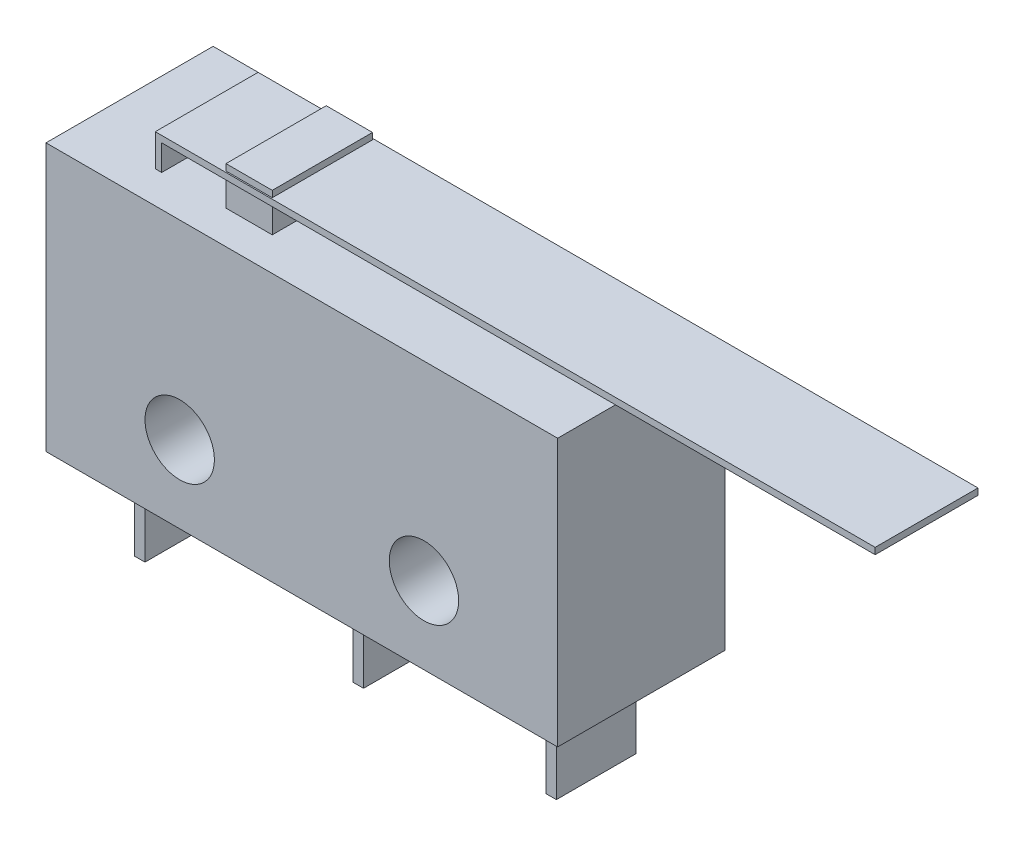
SolidWorks part; units mm, degrees
ref_plane "Plan de face" through (0, 0, 0) normal (0, 0, 1) x (1, 0, 0)
ref_plane "Plan de dessus" through (0, 0, 0) normal (0, 1, 0) x (1, 0, 0)
ref_plane "Plan de droite" through (0, 0, 0) normal (1, 0, 0) x (0, 0, -1)
sketch "Esquisse1" plane through (0, 0, 0) normal (0, 0, 1) x (1, 0, 0)
  line L1 (-9.95, 5.2) -> (9.95, 5.2)
  line L2 (-9.95, 5.2) -> (-9.95, -5.2)
  line L3 (-9.95, -5.2) -> (9.95, -5.2)
  line L4 (9.95, 5.2) -> (9.95, -5.2)
  point P4 (-9.95, 0)
  point P6 (0, 5.2)
  dimension "D1" = 19.9
  dimension "D2" = 10.4
extrude "Boss.-Extru.1" add sketch "Esquisse1" along normal mid plane 6.5
hole_wizard "Dégagement M2.51" positions "Esquisse2" profile "Esquisse3" hole size "M2.5" standard "DIN" end condition through all
sketch "Esquisse2" plane through (0, 0, 3.25) normal (0, 0, 1) x (1, 0, 0)
  line L0 (0, 0) -> (0, -2.7537) construction
  line L2 (-9.95, -5.2) -> (9.95, -5.2) construction
  point P2 (-4.75, -2.2)
  point P9 (4.75, -2.2)
  dimension "D1" = 9.5
  dimension "D2" = 3
sketch "Esquisse3" plane through (-4.75, -2.2, 3.25) normal (1, 0, 0) x (0, -1, 0)
  line L0 (0, 0) -> (0, 6.5)
  line L1 (0, 6.5) -> (1.35, 6.5)
  line L2 (1.35, 6.5) -> (1.35, 0)
  line L5 (1.35, 0) -> (0, 0)
  line L11 (0, -6.35) -> (0, 107.95) construction
  dimension "Diamètre du perçage jusqu'au prochain" = 2.7
  dimension "Profondeur du perçage jusqu'au prochain" = 6.5
sketch "Esquisse4" plane through (0, -5.2, 0) normal (0, -1, 0) x (1, 0, 0)
  line L0 (0, 0) -> (0, -1.7746) construction
  line L1 (0.3, 1.55) -> (0.7, 1.55)
  line L2 (0.3, 1.55) -> (0.3, -1.55)
  line L3 (0.3, -1.55) -> (0.7, -1.55)
  line L4 (0.7, 1.55) -> (0.7, -1.55)
  line L5 (8.2, -1.55) -> (7.8, -1.55)
  line L6 (-8.2, 1.55) -> (-7.8, 1.55)
  line L7 (-8.2, 1.55) -> (-8.2, -1.55)
  line L8 (-8.2, -1.55) -> (-7.8, -1.55)
  line L9 (-7.8, 1.55) -> (-7.8, -1.55)
  line L10 (7.8, 1.55) -> (7.8, -1.55)
  line L11 (8.2, 1.55) -> (7.8, 1.55)
  line L12 (8.2, 1.55) -> (8.2, -1.55)
  point P4 (0.3, 0)
  point P12 (-7.8, 0)
  dimension "D1" = 0.4
  dimension "D2" = 3.1
  dimension "D3" = 16
  dimension "D4" = 0.3
extrude "Boss.-Extru.2" add sketch "Esquisse4" along normal blind 3.5
sketch "Esquisse5" plane through (0, 5.2, 0) normal (0, 1, 0) x (1, 0, 0)
  line L0 (-9.95, -3.25) -> (-9.95, 3.25) construction
  line L1 (-2.45, 1.95) -> (-4.25, 1.95)
  line L2 (-2.45, 1.95) -> (-2.45, -1.95)
  line L3 (-2.45, -1.95) -> (-4.25, -1.95)
  line L4 (-4.25, 1.95) -> (-4.25, -1.95)
  point P5 (-2.45, 0)
  dimension "D1" = 1.8
  dimension "D2" = 3.9
  dimension "D3" = 5.7
extrude "Boss.-Extru.3" add sketch "Esquisse5" along normal blind 1.5
sketch "Esquisse6" plane through (0, 0, 0) normal (0, 0, 1) x (1, 0, 0)
  line L0 (-6.7, 5.2) -> (-6.7, 6.2)
  line L1 (9.95, 5.2) -> (-9.95, 5.2) construction
  line L2 (-6.7, 6.2) -> (21.05, 6.2)
  line L3 (21.05, 6.2) -> (21.05, 6.45)
  line L4 (21.05, 6.45) -> (-6.95, 6.45)
  line L5 (-6.95, 6.45) -> (-6.95, 5.2)
  line L6 (-6.95, 5.2) -> (-6.7, 5.2)
  dimension "D1" = 0.25
  dimension "D2" = 1
  dimension "D3" = 28
  dimension "D4" = 3
extrude "Boss.-Extru.4" add sketch "Esquisse6" along normal mid plane 4
